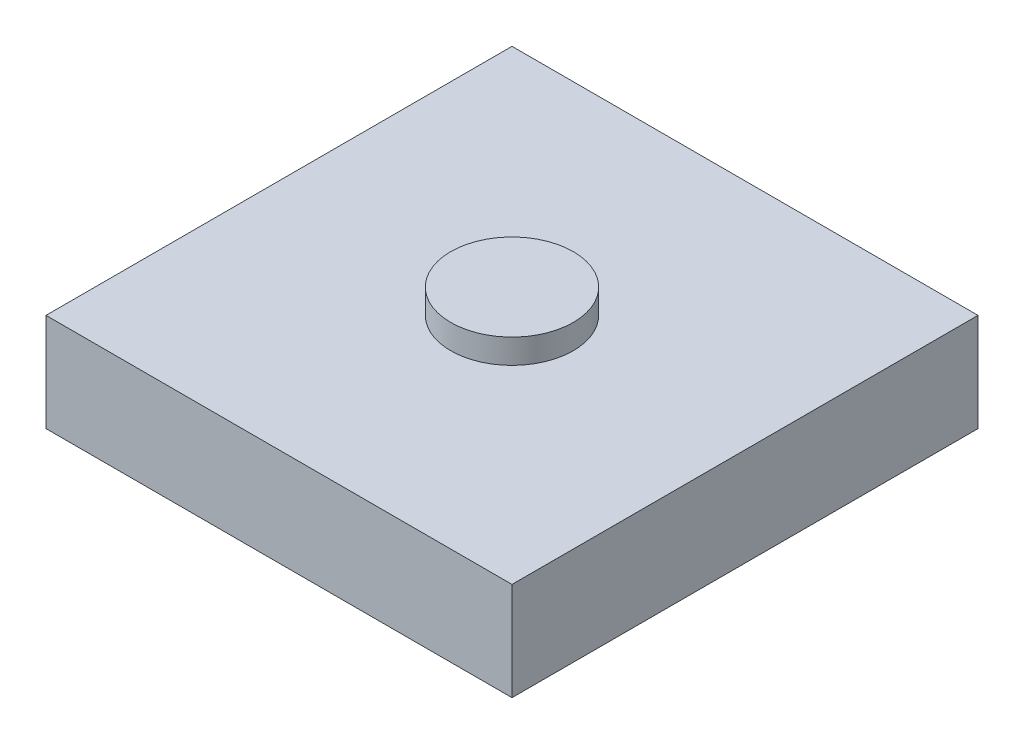
SolidWorks part; units mm, degrees
ref_plane "Front Plane" through (0, 0, 0) normal (0, 0, 1) x (1, 0, 0)
ref_plane "Top Plane" through (0, 0, 0) normal (0, 1, 0) x (1, 0, 0)
ref_plane "Right Plane" through (0, 0, 0) normal (1, 0, 0) x (0, 0, -1)
sketch "Sketch1" plane through (0, 0, 0) normal (0, 1, 0) x (1, 0, 0)
  line L1 (-12.065, -12.065) -> (12.065, -12.065)
  line L2 (-12.065, -12.065) -> (-12.065, 12.065)
  line L3 (-12.065, 12.065) -> (12.065, 12.065)
  line L4 (12.065, -12.065) -> (12.065, 12.065)
  line L5 (-12.065, -12.065) -> (12.065, 12.065) construction
  line L6 (-12.065, 12.065) -> (12.065, -12.065) construction
  point P0 (0, 0)
  dimension "D1" = 24.13
  dimension "D2" = 24.13
extrude "Boss-Extrude1" add sketch "Sketch1" along normal blind 5.08
sketch "Sketch2" plane through (0, 0, 0) normal (0, 1, 0) x (1, 0, 0)
  circle A0 centre (0, 0) radius 3.302
  dimension "D1" = 6.604
extrude "Cut-Extrude1" cut sketch "Sketch2" along normal blind 1.27
sketch "Sketch3" plane through (0, 5.08, 0) normal (0, 1, 0) x (1, 0, 0)
  circle A0 centre (0, 0) radius 3.175
  dimension "D1" = 6.35
extrude "Boss-Extrude2" add sketch "Sketch3" along normal blind 1.27
